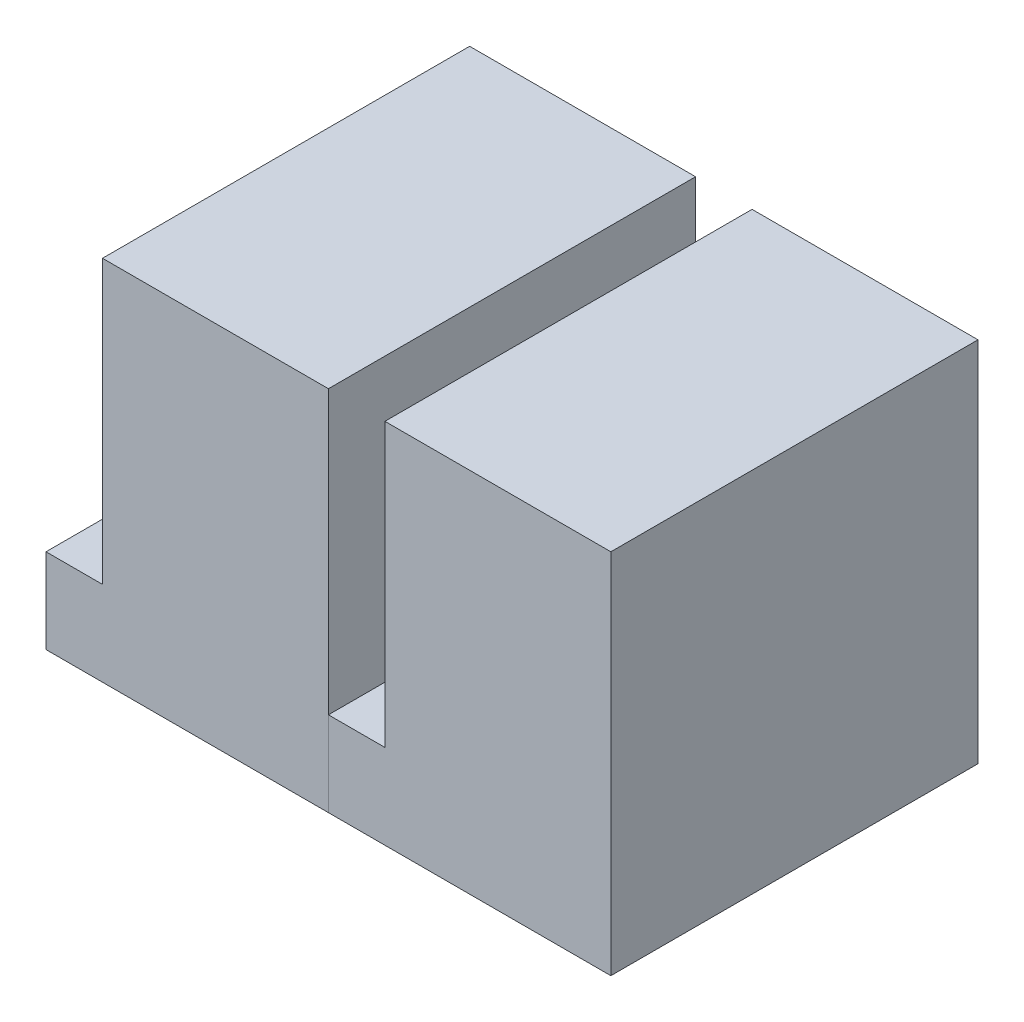
SolidWorks part; units mm, degrees
ref_plane "Front Plane" through (0, 0, 0) normal (0, 0, 1) x (1, 0, 0)
ref_plane "Top Plane" through (0, 0, 0) normal (0, 1, 0) x (1, 0, 0)
ref_plane "Right Plane" through (0, 0, 0) normal (1, 0, 0) x (0, 0, -1)
sketch "Sketch1" plane through (0, 0, 0) normal (0, 1, 0) x (1, 0, 0)
  line L1 (0, 0) -> (8, 0)
  line L2 (0, 0) -> (0, 13)
  line L3 (0, 13) -> (8, 13)
  line L4 (8, 0) -> (8, 13)
extrude "Boss-Extrude1" add sketch "Sketch1" along normal blind 13
sketch "Sketch2" plane through (0, 0, 0) normal (0, -1, 0) x (1, 0, 0)
  line L0 (8, 0) -> (8, -13) construction
  line L1 (1, -1) -> (7, -1)
  line L2 (1, -1) -> (1, -12)
  line L3 (1, -12) -> (7, -12)
  line L4 (7, -1) -> (7, -12)
  line L5 (0, -13) -> (0, 0) construction
  line L6 (0, 0) -> (8, 0) construction
  line L7 (8, -13) -> (0, -13) construction
  dimension "D1" = 1
  dimension "D2" = 1
  dimension "D3" = 1
  dimension "D4" = 1
extrude "Cut-Extrude1" cut sketch "Sketch2" against normal blind 12
sketch "Sketch3" plane through (0, 0, 0) normal (-1, 0, 0) x (0, 0, 1)
  line L0 (0, 13) -> (0, 0) construction
  line L1 (-13, 0) -> (0, 0)
  line L2 (-13, 0) -> (-13, 3)
  line L3 (-13, 3) -> (0, 3)
  line L4 (0, 0) -> (0, 3)
extrude "Boss-Extrude2" add sketch "Sketch3" along normal blind 2
pattern_linear "LPattern1" count 2 spacing 10 along (-1, 0, 0) of bodies 103
